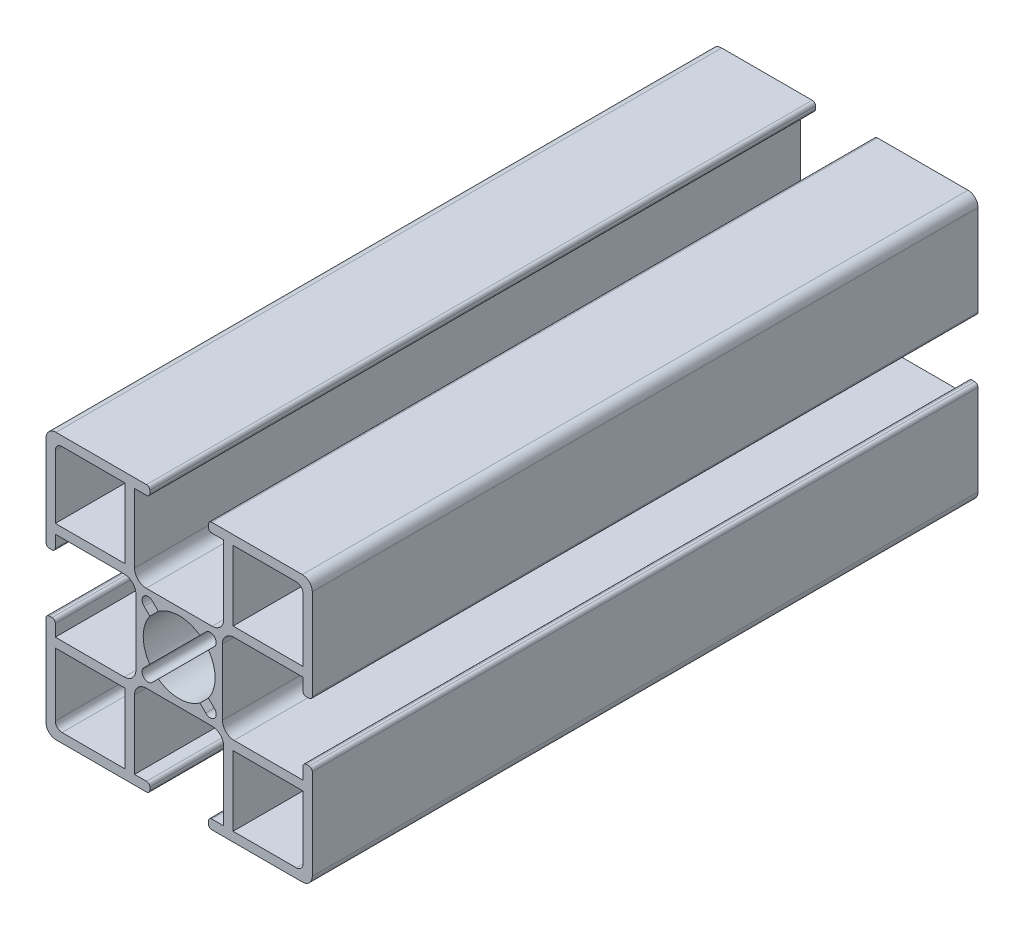
SolidWorks part; units mm, degrees
ref_plane "前视基准面" through (0, 0, 0) normal (0, 0, 1) x (1, 0, 0)
ref_plane "上视基准面" through (0, 0, 0) normal (0, 1, 0) x (1, 0, 0)
ref_plane "右视基准面" through (0, 0, 0) normal (1, 0, 0) x (0, 0, -1)
sketch "草图1" plane through (0, 0, 0) normal (0, 0, 1) x (1, 0, 0)
  line L0 (-18.78, 7.1542) -> (-18.78, 5.3542)
  line L1 (-19.28, 4.8542) -> (-19.68, 4.8542)
  line L2 (-20.18, 5.3542) -> (-20.18, 18.9542)
  line L3 (-18.68, 20.4542) -> (-5.08, 20.4542)
  line L4 (-4.58, 19.9542) -> (-4.58, 19.5542)
  line L5 (-5.08, 19.0542) -> (-6.88, 19.0542)
  line L6 (-8.28, 19.0542) -> (-17.78, 19.0542)
  line L7 (-18.78, 18.0542) -> (-18.78, 8.5542)
  line L8 (-18.78, 8.5542) -> (-8.28, 8.5542)
  line L9 (-18.78, 7.1542) -> (-8.43, 7.1542)
  line L10 (-8.28, 19.0542) -> (-8.28, 8.5542)
  line L11 (-6.88, 19.0542) -> (-6.88, 8.7042)
  line L12 (-5.13, 6.9542) -> (4.77, 6.9542)
  line L13 (6.32, 5.4042) -> (6.32, -4.4958)
  line L14 (4.77, -6.0458) -> (-5.13, -6.0458)
  line L15 (-6.68, -4.4958) -> (-6.68, 5.4042)
  line L16 (-4.5814, 3.5828) -> (-5.4438, 4.4452)
  line L17 (-3.3086, 4.8556) -> (-4.171, 5.718)
  line L18 (18.42, 7.1542) -> (18.42, 5.3542)
  line L19 (18.92, 4.8542) -> (19.32, 4.8542)
  line L20 (19.82, 5.3542) -> (19.82, 18.9542)
  line L21 (18.32, 20.4542) -> (4.72, 20.4542)
  line L22 (4.22, 19.9542) -> (4.22, 19.5542)
  line L23 (4.72, 19.0542) -> (6.52, 19.0542)
  line L24 (7.92, 19.0542) -> (17.42, 19.0542)
  line L25 (18.42, 18.0542) -> (18.42, 8.5542)
  line L26 (18.42, 8.5542) -> (7.92, 8.5542)
  line L27 (18.42, 7.1542) -> (8.07, 7.1542)
  line L28 (7.92, 19.0542) -> (7.92, 8.5542)
  line L29 (6.52, 19.0542) -> (6.52, 8.7042)
  line L30 (4.2214, 3.5828) -> (5.0838, 4.4452)
  line L31 (2.9486, 4.8556) -> (3.8877, 5.7947)
  line L32 (-18.78, -6.2458) -> (-18.78, -4.4458)
  line L33 (-19.28, -3.9458) -> (-19.68, -3.9458)
  line L34 (-20.18, -4.4458) -> (-20.18, -18.0458)
  line L35 (-18.68, -19.5458) -> (-5.08, -19.5458)
  line L36 (-4.58, -19.0458) -> (-4.58, -18.6458)
  line L37 (-5.08, -18.1458) -> (-6.88, -18.1458)
  line L38 (-8.28, -18.1458) -> (-17.78, -18.1458)
  line L39 (-18.78, -17.1458) -> (-18.78, -7.6458)
  line L40 (-18.78, -7.6458) -> (-8.28, -7.6458)
  line L41 (-18.78, -6.2458) -> (-8.43, -6.2458)
  line L42 (-8.28, -18.1458) -> (-8.28, -7.6458)
  line L43 (-6.88, -18.1458) -> (-6.88, -7.7958)
  line L44 (-4.5814, -2.6744) -> (-5.4438, -3.5368)
  line L45 (-3.3086, -3.9472) -> (-4.171, -4.8096)
  line L46 (18.42, -6.2458) -> (18.42, -4.4458)
  line L47 (18.92, -3.9458) -> (19.32, -3.9458)
  line L48 (19.82, -4.4458) -> (19.82, -18.0458)
  line L49 (18.32, -19.5458) -> (4.72, -19.5458)
  line L50 (4.22, -19.0458) -> (4.22, -18.6458)
  line L51 (4.72, -18.1458) -> (6.52, -18.1458)
  line L52 (7.92, -18.1458) -> (17.42, -18.1458)
  line L53 (18.42, -17.1458) -> (18.42, -7.6458)
  line L54 (18.42, -7.6458) -> (7.92, -7.6458)
  line L55 (18.42, -6.2458) -> (8.07, -6.2458)
  line L56 (7.92, -18.1458) -> (7.92, -7.6458)
  line L57 (6.52, -18.1458) -> (6.52, -7.7958)
  line L58 (4.2214, -2.6744) -> (5.0838, -3.5368)
  line L59 (2.9486, -3.9472) -> (3.811, -4.8096)
  arc A0 (-19.28, 4.8542) -> (-18.78, 5.3542) centre (-19.28, 5.3542) ccw
  arc A1 (-20.18, 5.3542) -> (-19.68, 4.8542) centre (-19.68, 5.3542) ccw
  arc A2 (-18.68, 20.4542) -> (-20.18, 18.9542) centre (-18.68, 18.9542) ccw
  arc A3 (-4.58, 19.9542) -> (-5.08, 20.4542) centre (-5.08, 19.9542) ccw
  arc A4 (-5.08, 19.0542) -> (-4.58, 19.5542) centre (-5.08, 19.5542) ccw
  arc A5 (-17.78, 19.0542) -> (-18.78, 18.0542) centre (-17.78, 18.0542) ccw
  arc A6 (-6.68, 5.4042) -> (-8.43, 7.1542) centre (-8.43, 5.4042) ccw
  arc A7 (-6.88, 8.7042) -> (-5.13, 6.9542) centre (-5.13, 8.7042) ccw
  arc A8 (-4.5814, 3.5828) -> (-4.5814, -2.6744) centre (-0.18, 0.4542) ccw
  arc A9 (-3.3086, -3.9472) -> (2.9486, -3.9472) centre (-0.18, 0.4542) ccw
  arc A10 (4.2214, -2.6744) -> (4.2214, 3.5828) centre (-0.18, 0.4542) ccw
  arc A11 (2.9486, 4.8556) -> (-3.3086, 4.8556) centre (-0.18, 0.4542) ccw
  arc A12 (-4.171, 5.718) -> (-5.4438, 4.4452) centre (-4.8458, 5.12) ccw
  arc A13 (18.42, 5.3542) -> (18.92, 4.8542) centre (18.92, 5.3542) ccw
  arc A14 (19.32, 4.8542) -> (19.82, 5.3542) centre (19.32, 5.3542) ccw
  arc A15 (19.82, 18.9542) -> (18.32, 20.4542) centre (18.32, 18.9542) ccw
  arc A16 (4.72, 20.4542) -> (4.22, 19.9542) centre (4.72, 19.9542) ccw
  arc A17 (4.22, 19.5542) -> (4.72, 19.0542) centre (4.72, 19.5542) ccw
  arc A18 (18.42, 18.0542) -> (17.42, 19.0542) centre (17.42, 18.0542) ccw
  arc A19 (8.07, 7.1542) -> (6.32, 5.4042) centre (8.07, 5.4042) ccw
  arc A20 (4.77, 6.9542) -> (6.52, 8.7042) centre (4.77, 8.7042) ccw
  arc A21 (5.0838, 4.4452) -> (3.8877, 5.7947) centre (4.4857, 5.12) ccw
  arc A22 (-18.78, -4.4458) -> (-19.28, -3.9458) centre (-19.28, -4.4458) ccw
  arc A23 (-19.68, -3.9458) -> (-20.18, -4.4458) centre (-19.68, -4.4458) ccw
  arc A24 (-20.18, -18.0458) -> (-18.68, -19.5458) centre (-18.68, -18.0458) ccw
  arc A25 (-5.08, -19.5458) -> (-4.58, -19.0458) centre (-5.08, -19.0458) ccw
  arc A26 (-4.58, -18.6458) -> (-5.08, -18.1458) centre (-5.08, -18.6458) ccw
  arc A27 (-18.78, -17.1458) -> (-17.78, -18.1458) centre (-17.78, -17.1458) ccw
  arc A28 (-8.43, -6.2458) -> (-6.68, -4.4958) centre (-8.43, -4.4958) ccw
  arc A29 (-5.13, -6.0458) -> (-6.88, -7.7958) centre (-5.13, -7.7958) ccw
  arc A30 (-5.4438, -3.5368) -> (-4.171, -4.8096) centre (-4.8458, -4.2115) ccw
  arc A31 (18.92, -3.9458) -> (18.42, -4.4458) centre (18.92, -4.4458) ccw
  arc A32 (19.82, -4.4458) -> (19.32, -3.9458) centre (19.32, -4.4458) ccw
  arc A33 (18.32, -19.5458) -> (19.82, -18.0458) centre (18.32, -18.0458) ccw
  arc A34 (4.22, -19.0458) -> (4.72, -19.5458) centre (4.72, -19.0458) ccw
  arc A35 (4.72, -18.1458) -> (4.22, -18.6458) centre (4.72, -18.6458) ccw
  arc A36 (17.42, -18.1458) -> (18.42, -17.1458) centre (17.42, -17.1458) ccw
  arc A37 (6.32, -4.4958) -> (8.07, -6.2458) centre (8.07, -4.4958) ccw
  arc A38 (6.52, -7.7958) -> (4.77, -6.0458) centre (4.77, -7.7958) ccw
  arc A39 (3.811, -4.8096) -> (5.0838, -3.5368) centre (4.4857, -4.2115) ccw
extrude "凸台-拉伸1" add sketch "草图1" along normal blind 100
